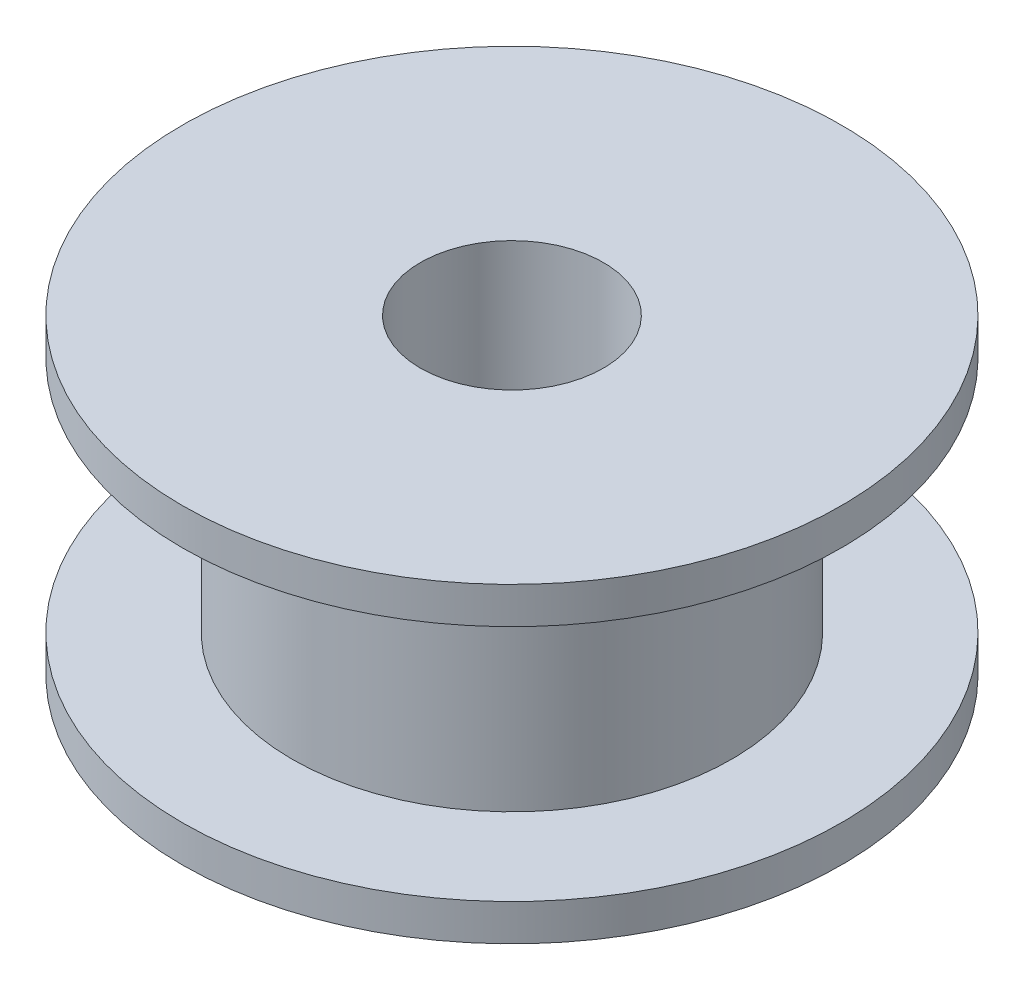
SolidWorks part; units mm, degrees
ref_plane "前视基准面" through (0, 0, 0) normal (0, 0, 1) x (1, 0, 0)
ref_plane "上视基准面" through (0, 0, 0) normal (0, 1, 0) x (1, 0, 0)
ref_plane "右视基准面" through (0, 0, 0) normal (1, 0, 0) x (0, 0, -1)
sketch "草图1" plane through (0, 0, 0) normal (0, 0, 1) x (1, 0, 0)
  line L0 (0, 4.25) -> (0, -4.25)
  line L1 (0, -4.25) -> (9, -4.25)
  line L2 (9, -4.25) -> (9, -3.25)
  line L3 (9, -3.25) -> (6, -3.25)
  line L4 (6, -3.25) -> (6, 3.25)
  line L5 (6, 3.25) -> (9, 3.25)
  line L6 (9, 3.25) -> (9, 4.25)
  line L7 (9, 4.25) -> (0, 4.25)
  line L8 (-1000, 0) -> (49000, 0) construction
  dimension "D1" = 9
  dimension "D2" = 6
  dimension "D3" = 8.5
  dimension "D4" = 6.5
revolve "旋转1" add sketch "草图1" angle 360 about L0
sketch "草图2" plane through (0, 4.25, 0) normal (0, 1, 0) x (1, 0, 0)
  circle A0 centre (0, 0) radius 2.5
  dimension "D1" = 5
extrude "切除-拉伸1" cut sketch "草图2" against normal up to next
